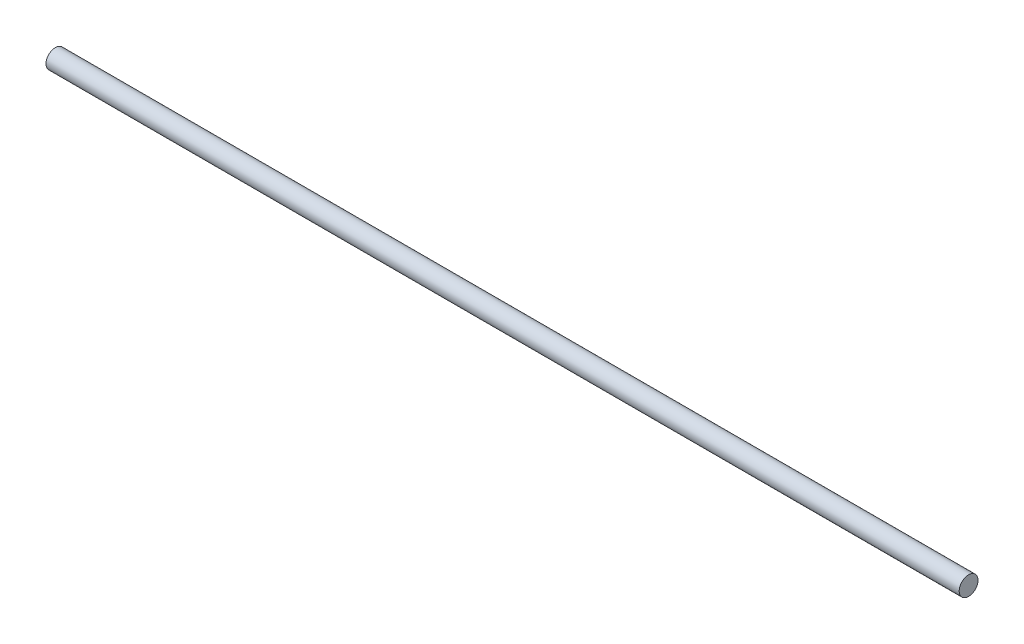
SolidWorks part; units mm, degrees
ref_plane "Front Plane" through (0, 0, 0) normal (0, 0, 1) x (1, 0, 0)
ref_plane "Top Plane" through (0, 0, 0) normal (0, 1, 0) x (1, 0, 0)
ref_plane "Right Plane" through (0, 0, 0) normal (1, 0, 0) x (0, 0, -1)
sketch "Sketch1" plane through (0, 0, 0) normal (0, 0, 1) x (1, 0, 0)
  line L0 (0, 0) -> (-143.6895, 0) construction
  line L2 (0, 0) -> (218.5, 0)
  line L3 (0, 0) -> (0, 2.25)
  line L4 (0, 2.25) -> (218.5, 2.25)
  line L5 (218.5, 0) -> (218.5, 2.25)
  dimension "D1" = 4.5
  dimension "D2" = 218.5
revolve "Revolve1" add sketch "Sketch1" angle 360 about L0
